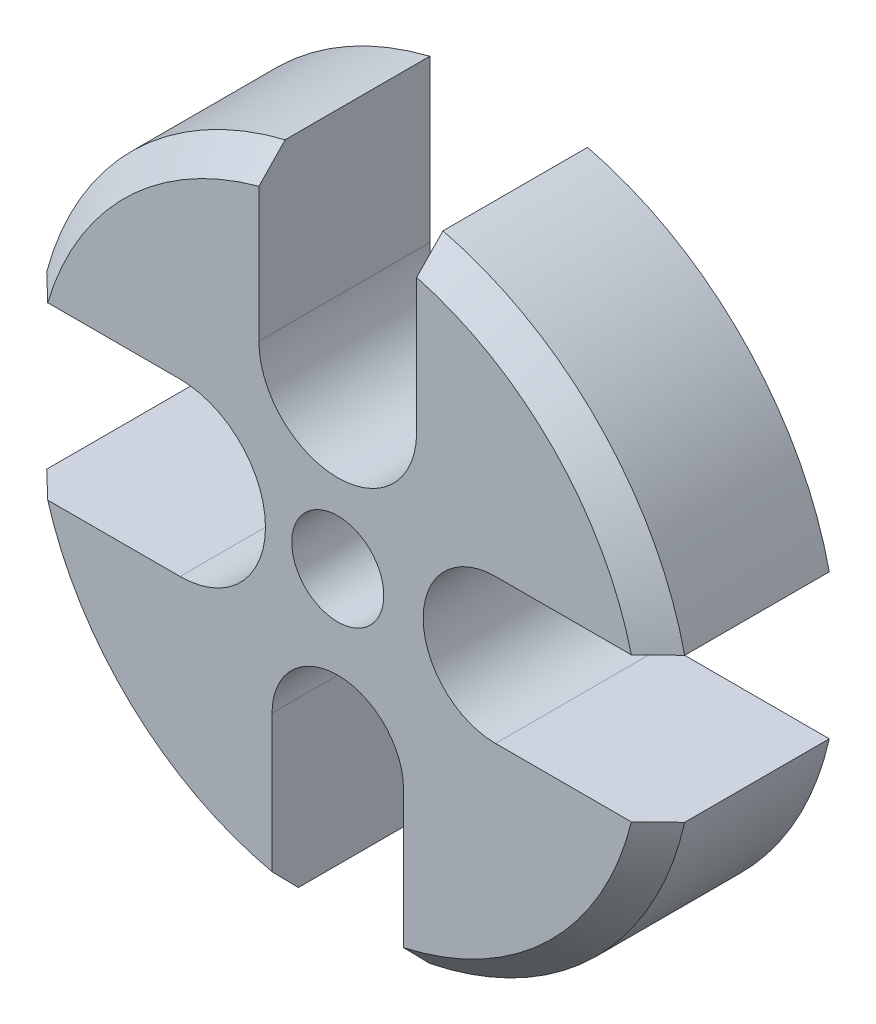
SolidWorks part; units mm, degrees
ref_plane "Front Plane" through (0, 0, 0) normal (0, 0, 1) x (1, 0, 0)
ref_plane "Top Plane" through (0, 0, 0) normal (0, 1, 0) x (1, 0, 0)
ref_plane "Right Plane" through (0, 0, 0) normal (1, 0, 0) x (0, 0, -1)
sketch "Sketch1" plane through (0, 0, 0) normal (0, 0, 1) x (1, 0, 0)
  line L0 (-41.1917, 0) -> (46.495, 0) construction
  line L1 (0, 30.5523) -> (0, -35.8367) construction
  line L2 (0, 25) -> (0, 12) construction
  line L3 (6, 25) -> (6, 12)
  line L4 (-6, 25) -> (-6, 12)
  line L5 (25, 0) -> (12, 0) construction
  line L6 (25, -5.5) -> (12, -5.5)
  line L7 (25, 5.5) -> (12, 5.5)
  line L8 (0, -12) -> (0, -25) construction
  line L9 (5, -12) -> (5, -25)
  line L10 (-5, -12) -> (-5, -25)
  line L11 (-12, 0) -> (-25, 0) construction
  line L12 (-12, -6.5) -> (-25, -6.5)
  line L13 (-12, 6.5) -> (-25, 6.5)
  circle A7 centre (0, 0) radius 3.5
  circle A8 centre (0, 0) radius 12 construction
  arc A9 (24.3875, 5.5) -> (6, 24.2693) centre (0, 0) ccw
  arc A10 (6, 25) -> (-6, 25) centre (0, 25) ccw
  arc A11 (-6, 12) -> (6, 12) centre (0, 12) ccw
  arc A12 (25, -5.5) -> (25, 5.5) centre (25, 0) ccw
  arc A13 (12, 5.5) -> (12, -5.5) centre (12, 0) ccw
  arc A14 (5, -12) -> (-5, -12) centre (0, -12) ccw
  arc A15 (-5, -25) -> (5, -25) centre (0, -25) ccw
  arc A16 (-12, -6.5) -> (-12, 6.5) centre (-12, 0) ccw
  arc A17 (-25, 6.5) -> (-25, -6.5) centre (-25, 0) ccw
  arc A18 (-24.1402, -6.5) -> (-5, -24.4949) centre (0, 0) ccw
  arc A19 (-6, 24.2693) -> (-24.1402, 6.5) centre (0, 0) ccw
  arc A20 (5, -24.4949) -> (24.3875, -5.5) centre (0, 0) ccw
  point P10 (0, 18.5)
  point P15 (18.5, 0)
  point P22 (0, -18.5)
  point P29 (-18.5, 0)
  dimension "D1" = 24
  dimension "D2" = 50
  dimension "D3" = 7
  dimension "D5" = 10
  dimension "D4" = 11
  dimension "D6" = 13
  dimension "D7" = 12
extrude "Boss-Extrude1" add sketch "Sketch1" along normal blind 13 contours L9 A20 L6 A13 L7 A9 L3 A11 L4 A19 L13 A16 L12 A18 L10 A14 A7
chamfer "Chamfer1" distance 2 angle 45 4 edges at (-17.4942, 17.8593, 13) (17.8584, 17.4951, 13) (17.4959, -17.8576, 13) (-17.1243, -18.2142, 13)
